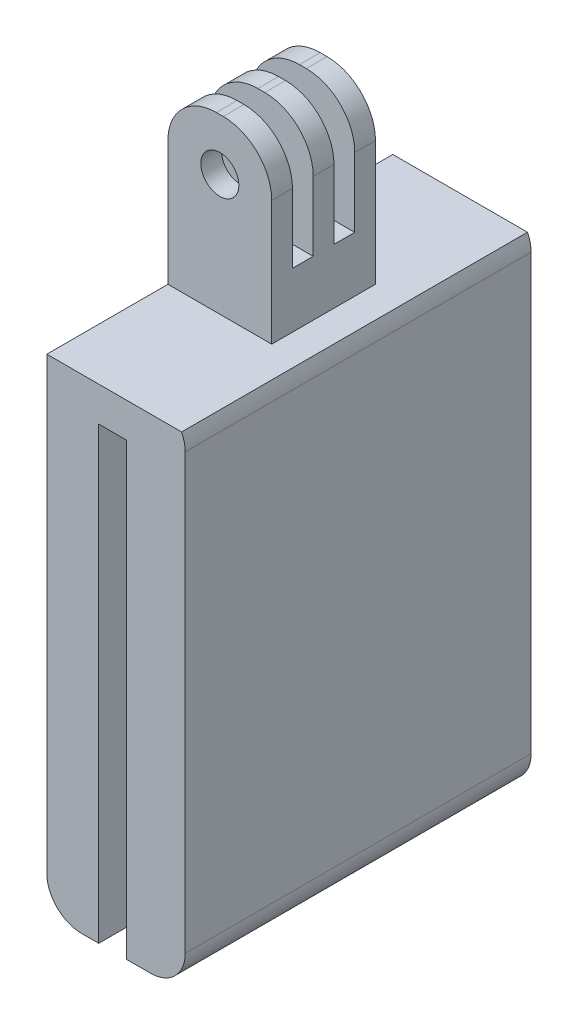
SolidWorks part; units mm, degrees
ref_plane "Front Plane" through (0, 0, 0) normal (0, 0, 1) x (1, 0, 0)
ref_plane "Top Plane" through (0, 0, 0) normal (0, 1, 0) x (1, 0, 0)
ref_plane "Right Plane" through (0, 0, 0) normal (1, 0, 0) x (0, 0, -1)
sketch "Sketch1" plane through (0, 0, 0) normal (0, 0, 1) x (1, 0, 0)
  line L1 (4.4721, 35) -> (0, 35)
  line L2 (5, 32.7639) -> (5, -30)
  line L3 (0, -35) -> (-10, -35)
  line L4 (-15, 35) -> (-15, -30)
  line L6 (0, 35) -> (0, 60)
  line L7 (0, 60) -> (-15, 60)
  line L8 (-15, 35) -> (-15, 60)
  line L9 (-3.5, 30) -> (-7.5, 30)
  line L10 (-3.5, 30) -> (-3.5, -30)
  line L11 (-3.5, -30) -> (-7.5, -30)
  line L12 (-7.5, 30) -> (-7.5, -30)
  arc A0 (-10, -35) -> (-15, -30) centre (-10, -30) cw
  arc A1 (5, -30) -> (0, -35) centre (0, -30) cw
  arc A2 (4.4721, 35) -> (5, 32.7639) centre (0, 32.7639) cw
  point P19 (0, 0)
  dimension "D5" = 5
  dimension "D1" = 15
  dimension "D2" = 20
  dimension "D3" = 25
  dimension "D4" = 70
  dimension "D7" = 35
  dimension "D8" = 60
  dimension "D9" = 5
  dimension "D10" = 4
  dimension "D11" = 7.5
extrude "Boss-Extrude1" add sketch "Sketch1" along normal blind 50
sketch "Sketch2" plane through (0, 0, 0) normal (1, 0, 0) x (0, 0, -1)
  line L0 (-50, 35) -> (0, 35) construction
  line L1 (0, 60) -> (-17.5, 60)
  line L2 (0, 60) -> (0, 35)
  line L3 (0, 35) -> (-17.5, 35)
  line L4 (-17.5, 60) -> (-17.5, 35)
  line L5 (-50, 60) -> (0, 60) construction
  line L6 (-50, 60) -> (-32.5, 60)
  line L7 (-50, 60) -> (-50, 35)
  line L8 (-50, 35) -> (-32.5, 35)
  line L9 (-32.5, 60) -> (-32.5, 35)
  line L10 (-29.5, 60) -> (-26.5, 60)
  line L11 (-29.5, 60) -> (-29.5, 43)
  line L12 (-29.5, 43) -> (-26.5, 43)
  line L13 (-26.5, 60) -> (-26.5, 43)
  line L15 (-20.5, 60) -> (-23.5, 60)
  line L16 (-20.5, 60) -> (-20.5, 43)
  line L17 (-20.5, 43) -> (-23.5, 43)
  line L18 (-23.5, 60) -> (-23.5, 43)
  dimension "D1" = 3
  dimension "D2" = 3
  dimension "D3" = 3
  dimension "D4" = 3
  dimension "D5" = 3
  dimension "D6" = 17.5
  dimension "D7" = 17
extrude "Cut-Extrude3" cut sketch "Sketch2" against normal up to next
sketch "Sketch3" plane through (0, 0, 32.5) normal (0, 0, 1) x (1, 0, 0)
  line L2 (-15, 60) -> (-15, 35) construction
  line L3 (-15, 60) -> (0, 60) construction
  circle A0 centre (-7.5, 52.5) radius 2.75
  point P2 (-7.8345, 54.5584)
  dimension "D1" = 5.5
  dimension "D2" = 7.5
  dimension "D3" = 7.5
extrude "Cut-Extrude4" cut sketch "Sketch3" against normal through all
sketch "Sketch5" plane through (0, 0, 50) normal (0, 0, 1) x (1, 0, 0)
  line L7 (-10, -35) -> (0, -35) construction
  line L8 (-7.5, -30) -> (-3.5, -30)
  line L9 (-7.5, -30) -> (-7.5, -35)
  line L10 (-7.5, -35) -> (-3.5, -35)
  line L11 (-3.5, -30) -> (-3.5, -35)
  dimension "D1" = 4
extrude "Cut-Extrude5" cut sketch "Sketch5" against normal through all
fillet "Fillet1" radius 7 6 edges at (-15, 60, 19) (-15, 60, 25) (-15, 60, 31) (0, 60, 19) (0, 60, 25) (0, 60, 31)
